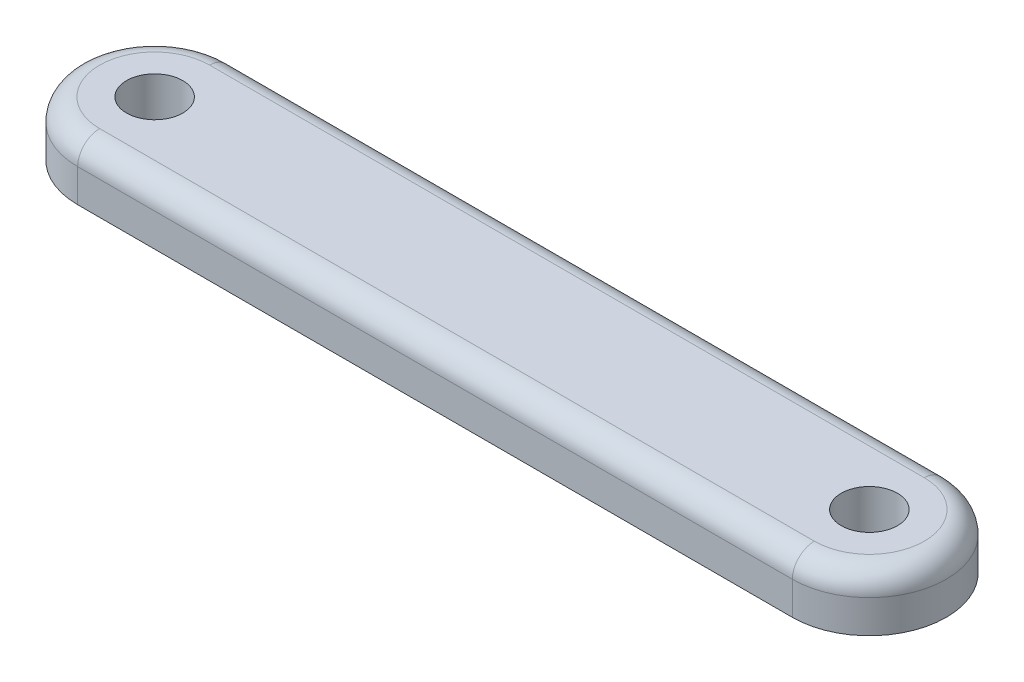
SolidWorks part; units mm, degrees
ref_plane "Front Plane" through (0, 0, 0) normal (0, 0, 1) x (1, 0, 0)
ref_plane "Top Plane" through (0, 0, 0) normal (0, 1, 0) x (1, 0, 0)
ref_plane "Right Plane" through (0, 0, 0) normal (1, 0, 0) x (0, 0, -1)
sketch "Sketch1" plane through (0, 0, 0) normal (0, 1, 0) x (1, 0, 0)
  line L0 (0, 3.556) -> (33.02, 3.556)
  line L1 (33.02, 0) -> (0, 0)
  line L2 (0, -3.556) -> (33.02, -3.556)
  circle A0 centre (0, 0) radius 1.3
  circle A1 centre (33.02, 0) radius 1.3
  arc A3 (0, 3.556) -> (0, -3.556) centre (0, 0) ccw
  arc A4 (33.02, 3.556) -> (33.02, -3.556) centre (33.02, 0) cw
  dimension "D2" = 2.6
  dimension "D1" = 33.02
  dimension "D3" = 3.556
extrude "Boss-Extrude1" add sketch "Sketch1" along normal blind 2.54
fillet "Fillet1" radius 1.016 4 edges at (-3.556, 2.54, 0) (16.51, 2.54, 3.556) (36.576, 2.54, 0) (16.51, 2.54, -3.556)
